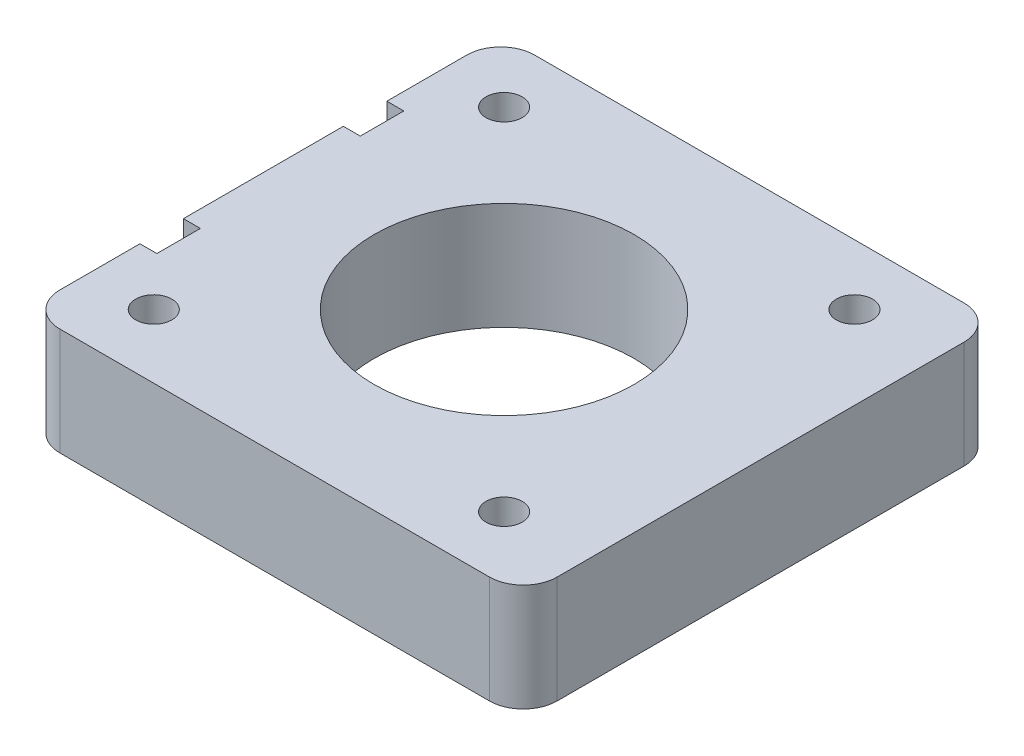
SolidWorks part; units mm, degrees
ref_plane "前视基准面" through (0, 0, 0) normal (0, 0, 1) x (1, 0, 0)
ref_plane "上视基准面" through (0, 0, 0) normal (0, 1, 0) x (1, 0, 0)
ref_plane "右视基准面" through (0, 0, 0) normal (1, 0, 0) x (0, 0, -1)
sketch "草图1" plane through (0, 0, 0) normal (0, 1, 0) x (1, 0, 0)
  line L1 (0, 0) -> (44, 0)
  line L2 (0, 0) -> (0, -42)
  line L3 (0, -42) -> (44, -42)
  line L4 (44, 0) -> (44, -42)
  dimension "D1" = 42
  dimension "D2" = 44
extrude "凸台-拉伸1" add sketch "草图1" along normal blind 9.5
sketch "草图2" plane through (0, 9.5, 0) normal (0, 1, 0) x (1, 0, 0)
  circle A0 centre (21.15, -20.85) radius 11.5
  dimension "D1" = 23
extrude "切除-拉伸1" cut sketch "草图2" against normal through all
fillet "圆角1" radius 3 4 edges at (44, 4.75, 0) (0, 4.75, 0) (0, 4.75, 42) (44, 4.75, 42)
sketch "草图5" plane through (0, 0, 0) normal (0, -1, 0) x (1, 0, 0)
  circle A0 centre (36.65, 36.35) radius 1.6
  circle A1 centre (5.65, 36.35) radius 1.6
  circle A2 centre (5.65, 5.35) radius 1.6
  circle A3 centre (36.65, 5.35) radius 1.6
  dimension "D1" = 3.2
extrude "切除-拉伸2" cut sketch "草图5" against normal through all
sketch "草图6" plane through (0, 0, 0) normal (-1, 0, 0) x (0, 0, 1)
  line L6 (39, 4.75) -> (3, 4.75) construction
  line L7 (39, 0) -> (39, 9.5) construction
  line L8 (3, 9.5) -> (3, 0) construction
sketch "草图7" plane through (0, 0, 0) normal (-1, 0, 0) x (0, 0, 1)
  line L0 (39, 4.75) -> (3, 4.75) construction
  line L1 (39, 0) -> (39, 9.5) construction
  line L2 (3, 9.5) -> (3, 0) construction
  circle A0 centre (30, 4.75) radius 1.925
  circle A1 centre (12, 4.75) radius 1.925
  dimension "D1" = 3.85
  dimension "D2" = 9
  dimension "D3" = 9
sketch "草图8" plane through (0, 0, 0) normal (-1, 0, 0) x (0, 0, 1)
  line L0 (3, 9.5) -> (39, 9.5) construction
  line L1 (10.075, 9.5) -> (13.925, 9.5)
  line L2 (10.075, 9.5) -> (10.075, 0)
  line L3 (10.075, 0) -> (13.925, 0)
  line L4 (13.925, 9.5) -> (13.925, 0)
  line L5 (3, 0) -> (39, 0) construction
  line L7 (28.075, 9.5) -> (31.925, 9.5)
  line L8 (28.075, 9.5) -> (28.075, 0)
  line L9 (28.075, 0) -> (31.925, 0)
  line L10 (31.925, 9.5) -> (31.925, 0)
extrude "切除-拉伸3" cut sketch "草图8" against normal blind 1.5
